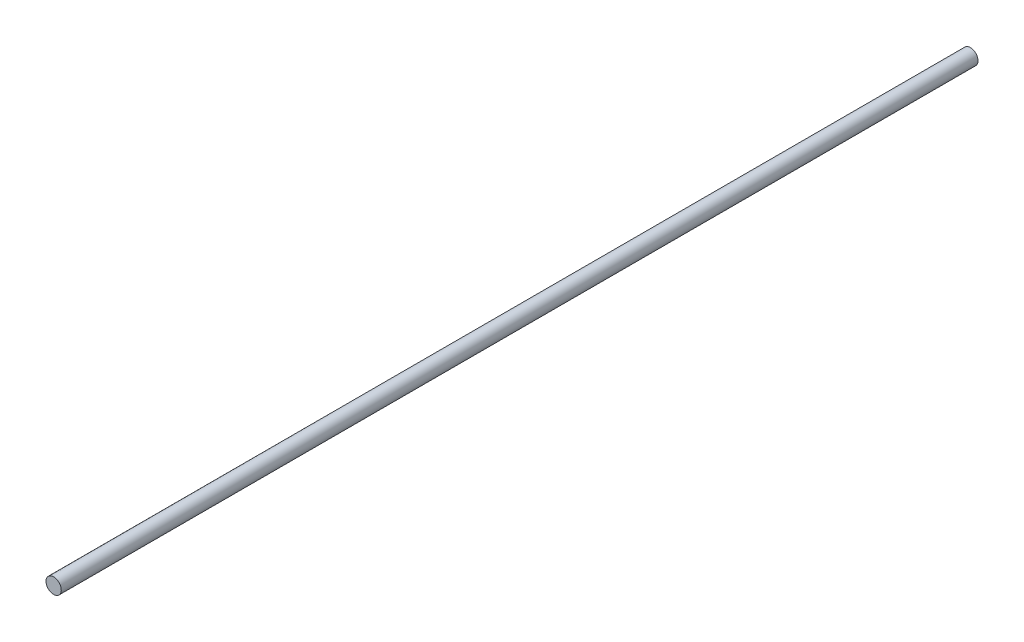
SolidWorks part; units mm, degrees
ref_plane "前视基准面" through (0, 0, 0) normal (0, 0, 1) x (1, 0, 0)
ref_plane "上视基准面" through (0, 0, 0) normal (0, 1, 0) x (1, 0, 0)
ref_plane "右视基准面" through (0, 0, 0) normal (1, 0, 0) x (0, 0, -1)
sketch "草图1" plane through (0, 0, 0) normal (0, 0, 1) x (1, 0, 0)
  circle A0 centre (0, 0) radius 5
  dimension "D1" = 10
extrude "凸台-拉伸1" add sketch "草图1" along normal blind 600
